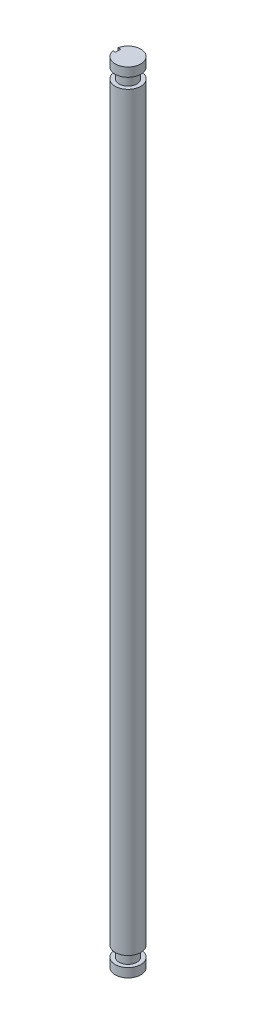
SolidWorks part; units mm, degrees
ref_plane "Front Plane" through (0, 0, 0) normal (1, 0, 0) x (0, 1, 0)
ref_plane "Top Plane" through (0, 0, 0) normal (0, 0, 1) x (0, 1, 0)
ref_plane "Right Plane" through (0, 0, 0) normal (0, 1, 0) x (-1, 0, 0)
sketch "Sketch1" plane through (0, 0, 0) normal (0, 0, 1) x (0, 1, 0)
  line L0 (-976.376, 0) -> (-976.376, 31.7309)
  line L1 (-976.376, 31.7309) -> (-954.024, 31.7309)
  line L2 (-954.024, 31.7309) -> (-954.024, 22.0218)
  line L3 (-954.024, 22.0218) -> (-928.2176, 22.0218)
  line L4 (-928.2176, 22.0218) -> (-928.2176, 31.7309)
  line L5 (-928.2176, 31.7309) -> (928.3446, 31.7309)
  line L6 (928.3446, 31.7309) -> (928.3446, 22.0218)
  line L7 (928.3446, 22.0218) -> (954.151, 22.0218)
  line L8 (954.151, 22.0218) -> (954.151, 31.7309)
  line L9 (954.151, 31.7309) -> (976.376, 31.7309)
  line L10 (976.376, 31.7309) -> (976.376, 0)
  line L11 (976.376, 0) -> (-976.376, 0)
  line L12 (-1001.776, 0) -> (1001.776, 0) construction
  dimension "D1" = 22.225
  dimension "D2" = 48.0314
  dimension "D3" = 1904.5936
  dimension "D4" = 1930.4
  dimension "D5" = 1952.752
  dimension "D6" = 9.7092
  dimension "D7" = 31.7309
revolve "Revolve1" add sketch "Sketch1" angle 360 about L12
sketch "Sketch2" plane through (0, 0, 0) normal (0, 1, 0) x (-1, 0, 0)
  line L1 (24.6062, -6.35) -> (88.0682, -6.35)
  line L2 (24.6062, -6.35) -> (24.6062, 6.35)
  line L3 (24.6062, 6.35) -> (88.0682, 6.35)
  line L4 (88.0682, -6.35) -> (88.0682, 6.35)
  dimension "D1" = 63.4619
  dimension "D2" = 12.7
extrude "Cut-Extrude2" cut sketch "Sketch2" along normal blind 1997.456 from offset 998.728
